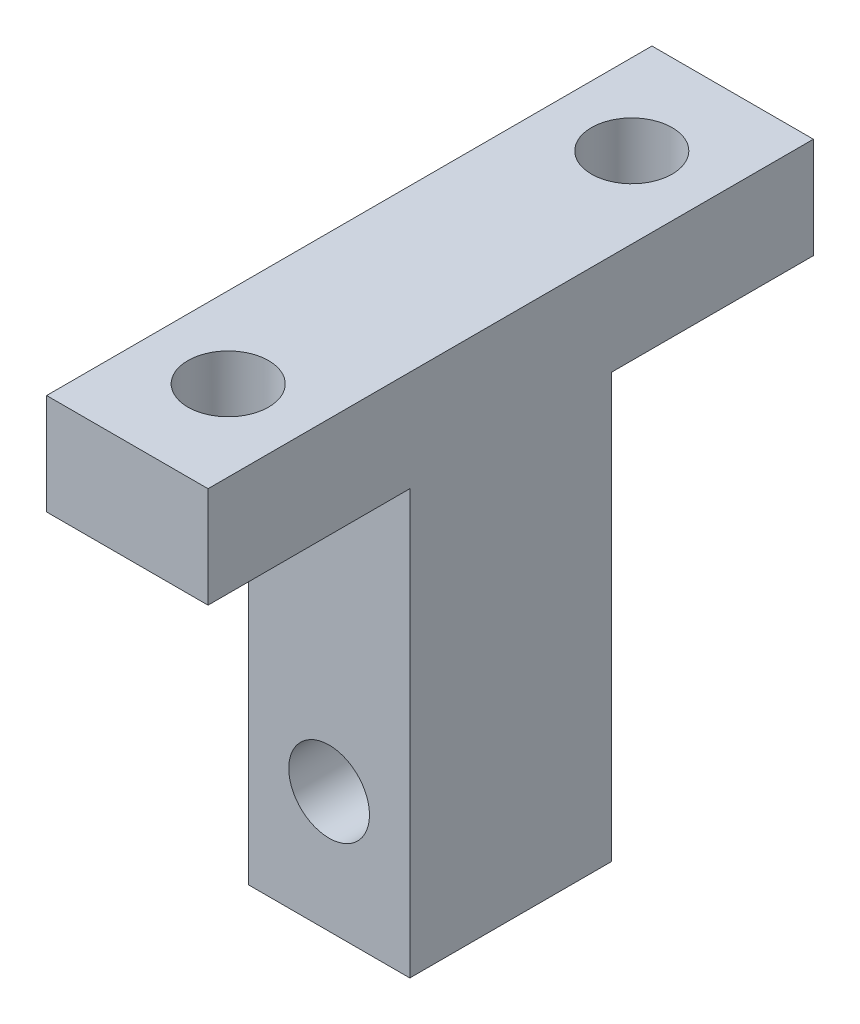
SolidWorks part; units mm, degrees
material "1060 合金"
ref_plane "前视基准面" through (0, 0, 0) normal (0, 0, 1) x (1, 0, 0)
ref_plane "上视基准面" through (0, 0, 0) normal (0, 1, 0) x (1, 0, 0)
ref_plane "右视基准面" through (0, 0, 0) normal (1, 0, 0) x (0, 0, -1)
sketch "草图1" plane through (0, 0, 0) normal (1, 0, 0) x (0, 0, -1)
  line L0 (-59.266, 0) -> (57.3175, 0) construction
  line L1 (-15, 0) -> (-15, -5)
  line L2 (-15, -5) -> (-5, -5)
  line L3 (-5, -5) -> (-5, -26)
  line L4 (-5, -26) -> (5, -26)
  line L5 (-15, 0) -> (0, 0)
  line L8 (0, 25.5575) -> (0, -39.3204) construction
  line L11 (15, 0) -> (0, 0)
  line L12 (5, -5) -> (5, -26)
  line L13 (15, -5) -> (5, -5)
  line L14 (15, 0) -> (15, -5)
  point P18 (0, -26)
  dimension "D1" = 5
  dimension "D4" = 26
  dimension "D5" = 15
  dimension "D6" = 10
  dimension "D7" = 5
extrude "凸台-拉伸1" add sketch "草图1" along normal mid plane 8
sketch "草图2" plane through (0, 0, 0) normal (0, 1, 0) x (1, 0, 0)
  line L0 (4, 0) -> (-4, 0) construction
  line L3 (4, 15) -> (-4, 15) construction
  line L4 (4, 15) -> (4, -15) construction
  line L5 (-4, 15) -> (-4, -15) construction
  circle A0 centre (0, 10) radius 2
  circle A1 centre (0, -10) radius 2
  dimension "D1" = 4
  dimension "D2" = 5
extrude "切除-拉伸1" cut sketch "草图2" against normal up to next
sketch "草图3" plane through (0, 0, 0) normal (0, 0, 1) x (1, 0, 0)
  circle A0 centre (0, -20) radius 2
  dimension "D1" = 4
  dimension "D2" = 20
extrude "切除-拉伸2" cut sketch "草图3" against normal through all both and the other way through all
